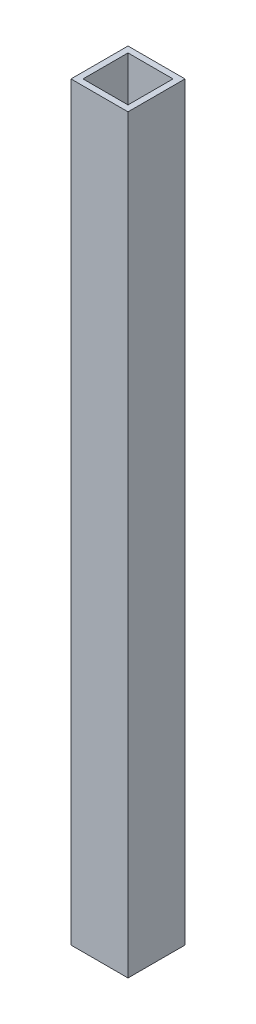
SolidWorks part; units mm, degrees
material "1060 Alloy"
ref_plane "Front Plane" through (0, 0, 0) normal (0, 0, 1) x (1, 0, 0)
ref_plane "Top Plane" through (0, 0, 0) normal (0, 1, 0) x (1, 0, 0)
ref_plane "Right Plane" through (0, 0, 0) normal (1, 0, 0) x (0, 0, -1)
sketch "Sketch1" plane through (0, 0, 0) normal (0, 1, 0) x (1, 0, 0)
  line L0 (-7.5, 7.5) -> (7.5, 7.5)
  line L1 (-9.5, -9.5) -> (9.5, -9.5)
  line L2 (-9.5, -9.5) -> (-9.5, 9.5)
  line L3 (-9.5, 9.5) -> (9.5, 9.5)
  line L4 (9.5, -9.5) -> (9.5, 9.5)
  line L5 (-9.5, -9.5) -> (9.5, 9.5) construction
  line L6 (-9.5, 9.5) -> (9.5, -9.5) construction
  line L7 (7.5, -7.5) -> (7.5, 7.5)
  line L8 (-7.5, -7.5) -> (7.5, -7.5)
  line L9 (-7.5, -7.5) -> (-7.5, 7.5)
  point P0 (0, 0)
  dimension "D1" = 19
  dimension "D2" = 19
  dimension "D3" = 2
extrude "Boss-Extrude1" add sketch "Sketch1" along normal blind 250
